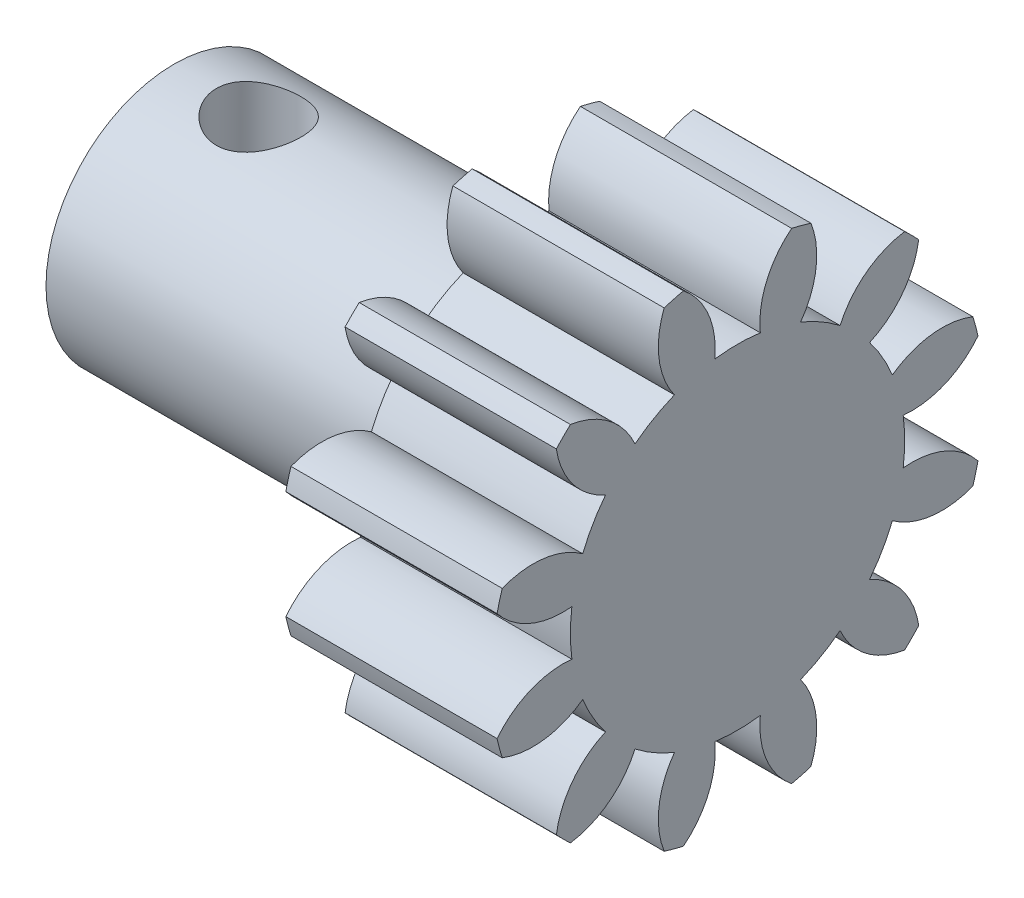
SolidWorks part; units mm, degrees
ref_plane "Plane1" through (0, 0, 0) normal (0, 0, 1) x (1, 0, 0)
ref_plane "Plane2" through (0, 0, 0) normal (0, 1, 0) x (1, 0, 0)
ref_plane "Plane3" through (0, 0, 0) normal (1, 0, 0) x (0, 0, -1)
sketch "HoldingSke" plane through (0, 0, 0) normal (0, 1, 0) x (1, 0, 0)
  line L0 (0, 0) -> (397.5192, -84.4953)
  line L1 (-15, 0) -> (100, 0) construction
  line L2 (0, 0) -> (-2.1039, 2.3779)
  line L3 (0, 0) -> (-11.863, 4.5341)
  line L4 (0, 0) -> (8.4473, 1.7955)
  line L5 (0, 0) -> (-47.5972, -17.7524)
  line L6 (0, 0) -> (-7.8959, -5.3274)
  line L7 (-2.1039, 2.3779) -> (8.8308, 51.9871)
  line L8 (-76.2, 54.61) -> (-69.596, 54.61)
  line L9 (-67.7845, 28.3722) -> (-49.3413, 33.142)
  line L10 (-76.2, 71.12) -> (104.1128, 71.12)
  line L11 (0, 0) -> (-9.525, 0)
  line L12 (-76.2, 101.6) -> (-76.1428, 101.6)
  line L13 (24.9733, 27.94) -> (52.9518, 28.4284)
  line L14 (24.9733, 27.94) -> (24.9746, 27.94)
  line L15 (24.9733, 27.94) -> (100.4006, 29.5858)
  circle A0 centre (0, 0) radius 3.175
  circle A1 centre (0, 0) radius 7.5394
  circle A2 centre (0, 0) radius 38.1
  circle A3 centre (0, 0) radius 3.175
  dimension "MHD" = 15.0787
  dimension "Hub_dia" = 76.2
  dimension "Bore" = 6.35
  dimension "MBD" = 6.35
  dimension "Num_teeth" = 12
  dimension "Pitch" = 406.4
  dimension "Overall_len" = 50.8
  dimension "Show_teeth" = 12
  dimension "Thickness" = 9.525
  dimension "OAL" = 50.8001
  dimension "T_dim" = 6.604
  dimension "Ap" = 14.5
  dimension "H" = 19.05
  dimension "Pitch_radius" = 180.3128
  dimension "Width" = 9.525
  dimension "Backlash" = 0.0571
  dimension "Addendum_fac" = 1
  dimension "Dedendum_fac" = 1.25
  dimension "Clearance_fac" = 0.25
  dimension "Dedendum_add" = 0.0013
sketch "BasProSke" plane through (0, 0, 0) normal (0, 1, 0) x (1, 0, 0)
  line L0 (-10, 0) -> (60, 0) construction
  line L1 (0, 0) -> (0, 11.1125)
  line L2 (0, 0) -> (9.525, 0)
  line L3 (9.525, 0) -> (9.525, 11.1125)
  line L4 (9.525, 11.1125) -> (0, 11.1125)
  dimension "Thickness" = 9.525
  dimension "Diameter" = 22.225
revolve "Base-Revolve" add sketch "BasProSke" angle 360 about L0
sketch "TooCutSke" plane through (0, 0, 0) normal (1, 0, 0) x (0, 0, -1)
  line L1 (0, 0) -> (0, 107) construction
  line L2 (0, 0) -> (-1.3431, 9.4298) construction
  line L3 (0, 0) -> (-4.8949, 18.2679) construction
  line L4 (-1.3431, 9.4298) -> (-2.4474, 9.1339) construction
  arc A0 (1.0269, 7.4691) -> (-1.0269, 7.4691) centre (0, 0) ccw
  arc A1 (2.4651, 10.8617) -> (-2.4651, 10.8617) centre (0, 0) ccw
  circle A2 centre (0, 0) radius 9.525 construction
  circle A3 centre (0, 0) radius 9.2216 construction
  arc A4 (-1.0269, 7.4691) -> (-2.4651, 10.8617) centre (-4.8164, 7.8638) ccw
  arc A5 (2.4651, 10.8617) -> (1.0269, 7.4691) centre (4.8164, 7.8638) ccw
  dimension "Root_dia" = 15.0787
  dimension "Overcut_dia" = 22.2758
  dimension "Pitch_dia" = 19.05
  dimension "Base_dia" = 18.4432
  dimension "Flank_rad" = 3.81
  dimension "Half_ang" = 15
  dimension "Half_CT" = 1.1432
extrude "ToothCut" cut sketch "TooCutSke" along normal through all
fillet "Breaks" [suppressed] radius 0.0318
fillet "RootFillets" [suppressed] radius 0.3981
pattern_circular "TeethCuts" count 12 every 30 about axis through (-10, 0, 0) along (1, 0, 0) of "ToothCut", "RootFillets", "Breaks"
sketch "HubNeaOneSke" plane through (0, 0, 0) normal (-1, 0, 0) x (0, 0, 1)
  circle A0 centre (0, 0) radius 7.5394
  dimension "Diameter" = 15.0787
extrude "HubNearOne" [suppressed] add sketch "HubNeaOneSke" along normal blind 41.2751
sketch "HubNeaBotSke" plane through (0, 0, 0) normal (-1, 0, 0) x (0, 0, 1)
  circle A0 centre (0, 0) radius 7.5394
  dimension "Diameter" = 15.0787
extrude "HubNearBoth" [suppressed] add sketch "HubNeaBotSke" along normal blind 20.6375
ref_plane "FarPln" through (9.525, 0, 0) normal (1, 0, 0) x (0, 0, -1)
sketch "HubFarSke" plane through (9.525, 0, 0) normal (1, 0, 0) x (0, 0, -1)
  circle A0 centre (0, 0) radius 7.5394
  dimension "Diameter" = 15.0787
extrude "HubFar" [suppressed] add sketch "HubFarSke" along normal blind 20.6375
sketch "BorSke" plane through (0, 0, 0) normal (1, 0, 0) x (0, 0, -1)
  circle A0 centre (0, 0) radius 3.175
  dimension "Diameter" = 6.35
extrude "Bore" cut sketch "BorSke" along normal mid plane 101.6001
sketch "KeySke" plane through (0, 0, 0) normal (1, 0, 0) x (0, 0, -1)
  line L0 (-0.127, 0) -> (-0.127, 3.429)
  line L1 (-0.127, 3.429) -> (0.127, 3.429)
  line L2 (0.127, 3.429) -> (0.127, 0)
  line L3 (0, 0) -> (0, 34) construction
  line L4 (-0.127, 0) -> (0.127, 0)
  dimension "Offset" = 3.429
  dimension "Width" = 0.254
extrude "Keyway" [suppressed] cut sketch "KeySke" along normal mid plane 101.6001
pattern_circular "Keyway2" [suppressed] count 2 every 90 about axis through (-10, 0, 0) along (1, 0, 0)
sketch "Sketch1" plane through (0, 0, 0) normal (1, 0, 0) x (0, 0, -1)
  circle A0 centre (0, 0) radius 9.525 construction
  dimension "D1" = 19.05
sketch "Sketch2" plane through (9.525, 0, 0) normal (1, 0, 0) x (0, 0, -1)
  circle A0 centre (0, 0) radius 7.5394
  arc A2 (-5.955, 4.6239) -> (-6.9819, 2.8452) centre (0, 0) ccw construction
extrude "Boss-Extrude1" add sketch "Sketch2" against normal blind 25.4
sketch "Sketch3" plane through (-15.875, 0, 0) normal (-1, 0, 0) x (0, 0, 1)
  line L0 (-1.778, 2.8575) -> (1.778, 2.8575)
  line L1 (0, 2.8575) -> (0, -3.3655) construction
  arc A0 (-1.778, 2.8575) -> (1.778, 2.8575) centre (0, 0) ccw
  dimension "D1" = 6.731
  dimension "D2" = 6.223
extrude "Cut-Extrude1" cut sketch "Sketch3" against normal blind 20
sketch "Sketch5" plane through (0, 2.8575, 0) normal (0, -1, 0) x (1, 0, 0)
  line L0 (-15.875, 7.5394) -> (-15.875, -7.5394) construction
  line L1 (0, -9.525) -> (0, 9.525) construction
  line L2 (-15.875, 0) -> (0, 0) construction
  circle A0 centre (-12.065, 0) radius 1.905
  dimension "D1" = 3.81
  dimension "D2" = 3.81
extrude "Cut-Extrude2" cut sketch "Sketch5" against normal through all
sketch "Sketch6" plane through (-15.875, 0, 0) normal (-1, 0, 0) x (0, 0, 1)
  circle A0 centre (0, 0) radius 5.7785
  circle A1 centre (0, 0) radius 12.7
  dimension "D1" = 11.557
  dimension "D2" = 25.4
extrude "Cut-Extrude3" cut sketch "Sketch6" against normal up to surface (15.875 mm away) up to face at (0, 2.4175, -9.0221)
equation "' \"Pitch@HoldingSke\" = 4"
equation "' \"Num_teeth@HoldingSke\" = 12"
equation "' \"Ap@HoldingSke\" =  20"
equation "' \"Ap@HoldingSke\" = 20"
equation "' \"Width@HoldingSke\" = 0.5"
equation "' \"Hub_dia@HoldingSke\"= 1"
equation "' \"Hub_dia@HoldingSke\" = 1"
equation "' \"Overall_len@HoldingSke\" = 1.0"
equation "' \"Bore@HoldingSke\" = 0.75"
equation "' \"T_dim@HoldingSke\" = 0.85"
equation "' \"Width@KeySke\" = 0.25"
equation "' \"Show_teeth@HoldingSke\" = 13"
equation "' \"Backlash@HoldingSke\" = 0.009"
equation "' \"Addendum_fac@HoldingSke\" = 1.0"
equation "' \"Dedendum_fac@HoldingSke\" = 1.25"
equation "' \"Dedendum_add@HoldingSke\" = 0.00005"
equation "' \"Clearance_fac@HoldingSke\" = 0.25"
equation "' \"Pitch@HoldingSke\" = 0.5"
equation "' \"Num_teeth@HoldingSke\" = 23"
equation "' \"Show_teeth@HoldingSke\" = 23"
equation "' \"Backlash@HoldingSke\" = 0.0375"
equation "\"Overcut_dia@TooCutSke\" = (\"Num_teeth@HoldingSke\" + 2 * \"Addendum_fac@HoldingSke\") / \"Pitch@HoldingSke\" + 0.002"
equation "\"Pitch_dia@TooCutSke\" = \"Num_teeth@HoldingSke\" / \"Pitch@HoldingSke\""
equation "\"Base_dia@TooCutSke\" = \"Num_teeth@HoldingSke\" / \"Pitch@HoldingSke\" * cos((\"Ap@HoldingSke\"  * 3.14159265 / 180))"
equation "\"Root_dia@TooCutSke\" = (\"Num_teeth@HoldingSke\" + 2) / \"Pitch@HoldingSke\" - 2 * (\"Addendum_fac@HoldingSke\" + \"Dedendum_fac@HoldingSke\") / \"Pitch@HoldingSke\" - \"Dedendum_add@HoldingSke\" * 2"
equation "\"Half_ang@TooCutSke\" = 180 / \"Num_teeth@HoldingSke\""
equation "\"Half_CT@TooCutSke\" = \"Num_teeth@HoldingSke\" / \"Pitch@HoldingSke\" * sin((3.14159265 / 2 / \"Num_teeth@HoldingSke\")) / 2 - 7 * \"Backlash@HoldingSke\" / 4"
equation "\"Flank_rad@TooCutSke\" = \"Num_teeth@HoldingSke\" / \"Pitch@HoldingSke\" / 5"
equation "\"Radius@RootFillets\" = \"Clearance_fac@HoldingSke\" / \"Pitch@HoldingSke\" + \"Dedendum_add@HoldingSke\""
equation "\"Break_rad@Breaks\" = 0.02 / \"Pitch@HoldingSke\""
equation "\"Thickness@HoldingSke\" = \"Width@HoldingSke\""
equation "\"OAL@HoldingSke\" = \"Thickness@HoldingSke\""
equation "\"MHD@HoldingSke\" = (\"Num_teeth@HoldingSke\" + 2) / \"Pitch@HoldingSke\" - 2 * (\"Addendum_fac@HoldingSke\" + \"Dedendum_fac@HoldingSke\")  / \"Pitch@HoldingSke\" - \"Dedendum_add@HoldingSke\" * 2"
equation "\"MBD@HoldingSke\" = (\"Num_teeth@HoldingSke\" + 2) / \"Pitch@HoldingSke\" - 2 * (\"Addendum_fac@HoldingSke\" + \"Dedendum_fac@HoldingSke\")  / \"Pitch@HoldingSke\" - \"Dedendum_add@HoldingSke\" * 2 - 0.002"
equation "\"MHD@HoldingSke\" = ((sgn( \"MHD@HoldingSke\" - \"Hub_dia@HoldingSke\" )-1)*( \"MHD@HoldingSke\" - \"Hub_dia@HoldingSke\" ))/-2+ \"Hub_dia@HoldingSke\""
equation "\"MBD@HoldingSke\" = ((sgn( \"MBD@HoldingSke\" - \"Bore@HoldingSke\" )-1)*( \"MBD@HoldingSke\" - \"Bore@HoldingSke\" ))/-2+ \"Bore@HoldingSke\""
equation "\"OAL@HoldingSke\" = ((sgn( \"OAL@HoldingSke\" - \"Overall_len@HoldingSke\" )+1)*( \"OAL@HoldingSke\" - \"Overall_len@HoldingSke\" ))/2 + \"Overall_len@HoldingSke\" + 0.000002"
equation "\"Num_teeth@TeethCuts\" = int( \"Show_teeth@HoldingSke\" ) + 1"
equation "\"Num_teeth@TeethCuts\" = ((sgn( \"Num_teeth@TeethCuts\" - \"Num_teeth@HoldingSke\" )-1)*( \"Num_teeth@TeethCuts\" - \"Num_teeth@HoldingSke\" ))/-2+ \"Num_teeth@HoldingSke\""
equation "\"Num_teeth@TeethCuts\" = ((sgn( \"Num_teeth@TeethCuts\" - 2.0)+1)*( \"Num_teeth@TeethCuts\" - 2.0))/2 +2.0"
equation "\"Angle@TeethCuts\" = 360.0 / \"Num_teeth@HoldingSke\""
equation "\"Diameter@BasProSke\" = (\"Num_teeth@HoldingSke\" + 2 * \"Addendum_fac@HoldingSke\") / \"Pitch@HoldingSke\""
equation "\"Thickness@BasProSke\"  = \"Thickness@HoldingSke\""
equation "' \"Fillet_rad@BasProSke\" =  \"Thickness@HoldingSke\" * 0.05"
equation "' \"Fillet_rad@BasProSke\" = \"Thickness@HoldingSke\" * 0.05"
equation "\"MHD@HoldingSke\" = ((sgn( \"MHD@HoldingSke\" - \"Root_dia@TooCutSke\" )-1)*( \"MHD@HoldingSke\" - \"Root_dia@TooCutSke\" ))/-2+ \"Root_dia@TooCutSke\""
equation "\"Diameter@HubNeaOneSke\" = \"MHD@HoldingSke\""
equation "\"Length@HubNearOne\" = \"OAL@HoldingSke\" - \"Thickness@BasProSke\""
equation "\"Diameter@HubNeaBotSke\" = \"MHD@HoldingSke\""
equation "\"Length@HubNearBoth\" = ( \"OAL@HoldingSke\" - \"Thickness@BasProSke\" ) / 2.0"
equation "\"Thickness@FarPln\" = \"Thickness@BasProSke\""
equation "\"Diameter@HubFarSke\" = \"MHD@HoldingSke\""
equation "\"Length@HubFar\" = ( \"OAL@HoldingSke\" - \"Thickness@BasProSke\" ) / 2.0"
equation "\"Diameter@BorSke\" = \"MBD@HoldingSke\""
equation "\"D1@Bore\" = \"OAL@HoldingSke\" * 2.0"
equation "\"D1@Keyway\" = \"OAL@HoldingSke\" * 2.0"
equation "\"Offset@KeySke\" = \"T_dim@HoldingSke\" - \"MBD@HoldingSke\" / 2.0"
